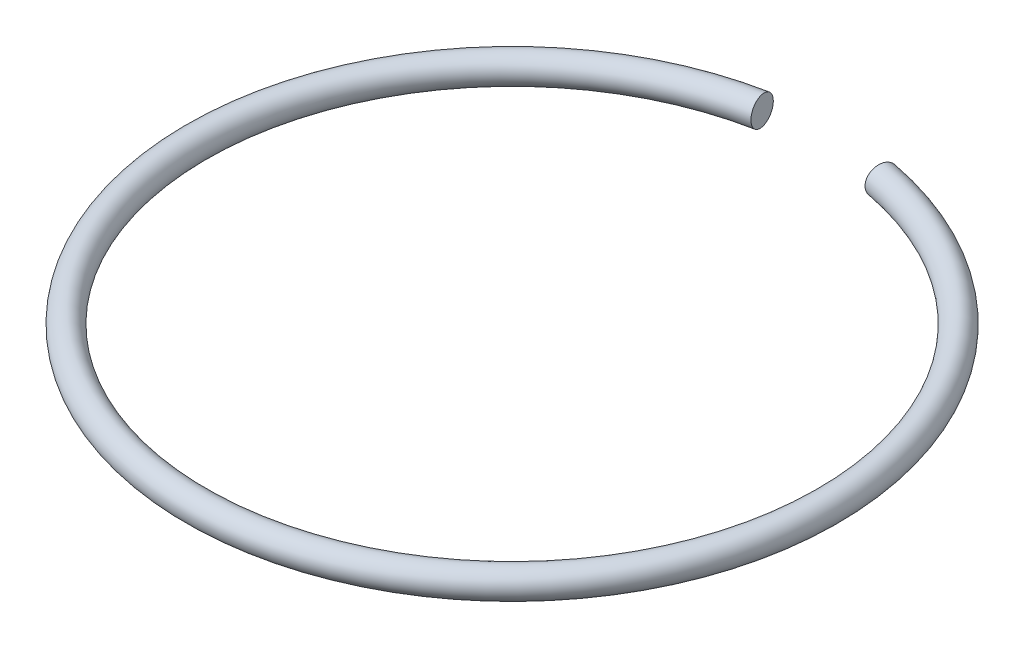
SolidWorks part; units mm, degrees
ref_plane "Plano frontal" through (0, 0, 0) normal (0, 0, 1) x (1, 0, 0)
ref_plane "Plano superior" through (0, 0, 0) normal (0, 1, 0) x (1, 0, 0)
ref_plane "Plano direito" through (0, 0, 0) normal (1, 0, 0) x (0, 0, -1)
sketch "Esboço1" plane through (0, 0, 0) normal (0, 0, 1) x (1, 0, 0)
  line L0 (0, 0) -> (0, 19.2741) construction
  circle A0 centre (-33.5, 0) radius 1.5
  dimension "D1" = 3
  dimension "D2" = 33.5
revolve "Revolução1" add sketch "Esboço1" angle 360 about L0
sketch "Esboço2" plane through (0, 0, 0) normal (0, 1, 0) x (1, 0, 0)
  line L0 (-6.75, 35) -> (6.75, 35)
  line L1 (0, 0) -> (0, 35) construction
  line L2 (-6.75, 35) -> (0, 0)
  line L3 (0, 0) -> (6.75, 35)
  circle A0 centre (0, 0) radius 35 construction
  dimension "D1" = 13.5
extrude "Corte-extrusão1" cut sketch "Esboço2" against normal through all and the other way through all
